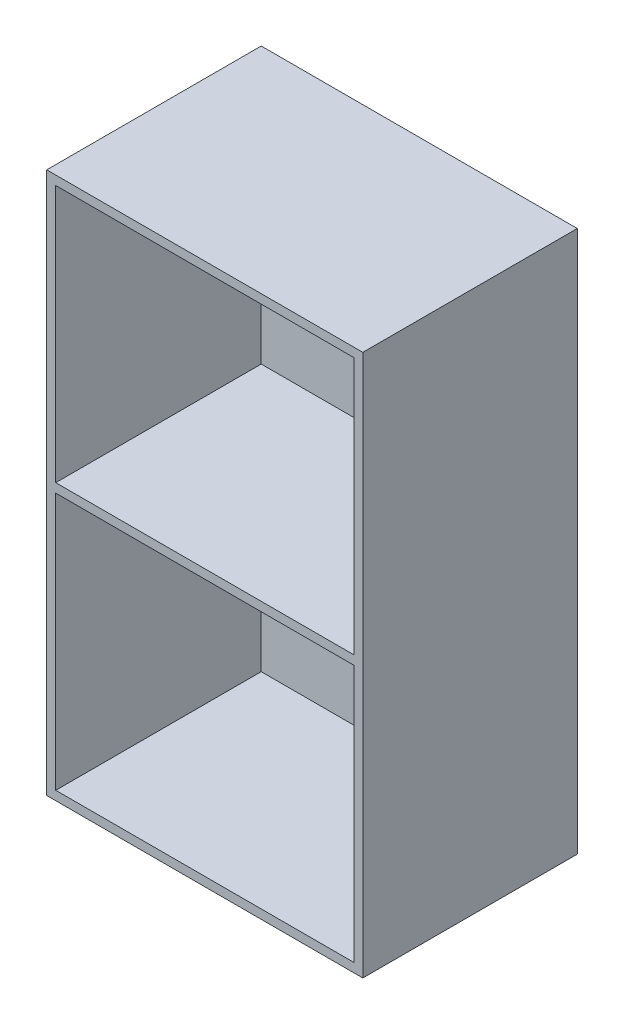
SolidWorks part; units mm, degrees
material "ﾁｰｸ材"
ref_plane "正面" through (0, 0, 0) normal (0, 0, 1) x (1, 0, 0)
ref_plane "平面" through (0, 0, 0) normal (0, 1, 0) x (1, 0, 0)
ref_plane "右側面" through (0, 0, 0) normal (1, 0, 0) x (0, 0, -1)
sketch "ｽｹｯﾁ1" plane through (0, 0, 0) normal (0, 0, 1) x (1, 0, 0)
  line L1 (-210, 360) -> (210, 360)
  line L2 (-210, 360) -> (-210, -360)
  line L3 (-210, -360) -> (210, -360)
  line L4 (210, 360) -> (210, -360)
  line L5 (-210, 360) -> (210, -360) construction
  line L6 (-210, -360) -> (210, 360) construction
  point P0 (0, 0)
  dimension "D1" = 720
  dimension "42" = 420
extrude "ﾎﾞｽ - 押し出し1" add sketch "ｽｹｯﾁ1" along normal blind 12
sketch "ｽｹｯﾁ2" plane through (0, 0, 12) normal (0, 0, 1) x (1, 0, 0)
  line L0 (-198, 348) -> (-198, 6)
  line L1 (-210, 360) -> (210, 360)
  line L2 (-210, 360) -> (-210, -360)
  line L3 (-210, -360) -> (210, -360)
  line L4 (210, 360) -> (210, -360)
  line L5 (-210, 360) -> (210, -360) construction
  line L6 (-210, -360) -> (210, 360) construction
  line L7 (-198, -348) -> (198, -348)
  line L8 (198, 348) -> (198, 6)
  line L9 (-198, 348) -> (198, 348)
  line L10 (-198, 6) -> (198, 6)
  line L11 (-198, -6) -> (198, -6)
  line L12 (-198, -6) -> (-198, -348)
  line L13 (-198, 348) -> (-198, -348) construction
  line L14 (198, -6) -> (198, -348)
  line L15 (198, 348) -> (198, -348) construction
  point P0 (0, 0)
  dimension "D1" = 12
  dimension "D2" = 6
  dimension "D3" = 6
extrude "ﾎﾞｽ - 押し出し2" add sketch "ｽｹｯﾁ2" along normal blind 273
